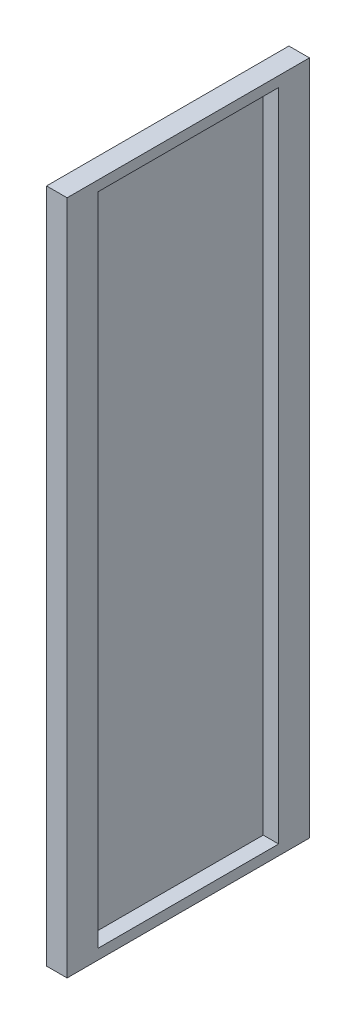
SolidWorks part; units mm, degrees
ref_plane "Front Plane" through (0, 0, 0) normal (0, 0, 1) x (1, 0, 0)
ref_plane "Top Plane" through (0, 0, 0) normal (0, 1, 0) x (1, 0, 0)
ref_plane "Right Plane" through (0, 0, 0) normal (1, 0, 0) x (0, 0, -1)
sketch "Sketch1" plane through (0, 0, 0) normal (0, 1, 0) x (1, 0, 0)
  line L1 (12.7, -149.86) -> (-12.7, -149.86)
  line L2 (12.7, -149.86) -> (12.7, 149.86)
  line L3 (12.7, 149.86) -> (-12.7, 149.86)
  line L4 (-12.7, -149.86) -> (-12.7, 149.86)
  line L5 (12.7, -149.86) -> (-12.7, 149.86) construction
  line L6 (12.7, 149.86) -> (-12.7, -149.86) construction
  point P0 (0, 0)
  dimension "D1" = 25.4
  dimension "D2" = 299.72
extrude "Boss-Extrude1" add sketch "Sketch1" along normal mid plane 835.66
sketch "Sketch2" plane through (12.7, 0, 0) normal (1, 0, 0) x (0, 0, -1)
  line L0 (-149.86, 417.83) -> (149.86, 417.83) construction
  line L1 (111.76, -405.13) -> (-111.76, -405.13)
  line L2 (111.76, -405.13) -> (111.76, 405.13)
  line L3 (111.76, 405.13) -> (-111.76, 405.13)
  line L4 (-111.76, -405.13) -> (-111.76, 405.13)
  line L5 (111.76, -405.13) -> (-111.76, 405.13) construction
  line L6 (111.76, 405.13) -> (-111.76, -405.13) construction
  line L7 (-149.86, 417.83) -> (-149.86, -417.83) construction
  point P0 (0, 0)
  dimension "D1" = 12.7
  dimension "D2" = 38.1
extrude "Cut-Extrude1" cut sketch "Sketch2" against normal blind 19.05
sketch "Sketch3" plane through (-12.7, 0, 0) normal (-1, 0, 0) x (0, 0, 1)
  line L0 (-149.86, 417.83) -> (149.86, 417.83) construction
  line L1 (143.51, 172.72) -> (118.11, 172.72)
  line L2 (143.51, 172.72) -> (143.51, 290.83)
  line L3 (143.51, 290.83) -> (118.11, 290.83)
  line L4 (118.11, 172.72) -> (118.11, 290.83)
  line L5 (149.86, 417.83) -> (149.86, -417.83) construction
  line L6 (-149.86, -417.83) -> (149.86, -417.83) construction
  dimension "D1" = 127
  dimension "D2" = 6.35
  dimension "D3" = 590.55
  dimension "D4" = 25.4
extrude "Cut-Extrude2" cut sketch "Sketch3" against normal blind 12.7
